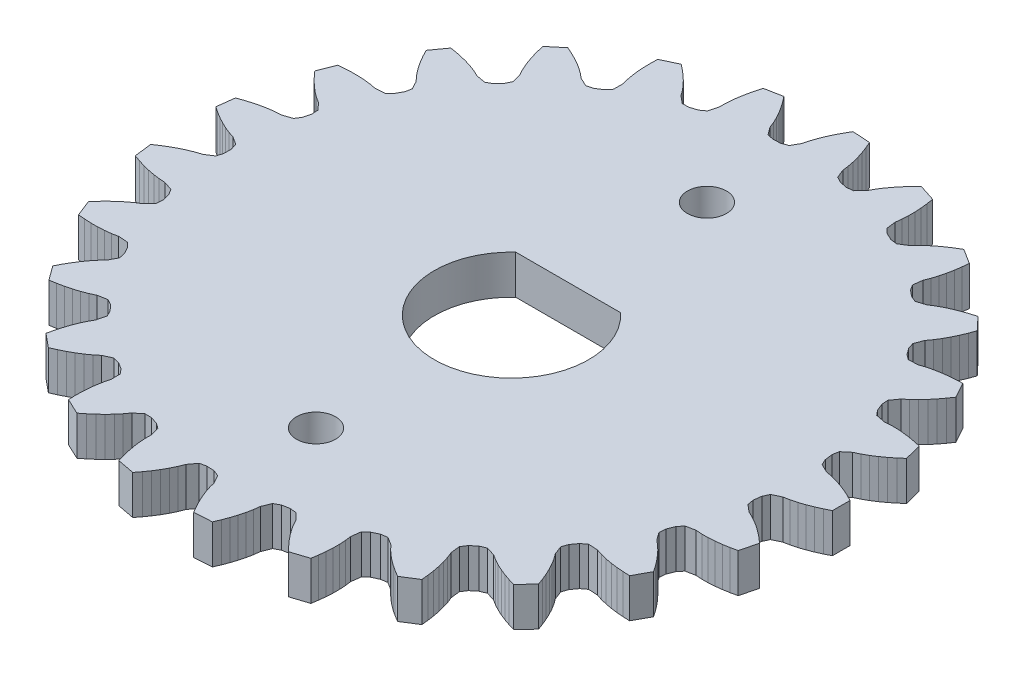
SolidWorks part; units mm, degrees
ref_plane "Спереди" through (0, 0, 0) normal (0, 0, 1) x (1, 0, 0)
ref_plane "Сверху" through (0, 0, 0) normal (0, 1, 0) x (1, 0, 0)
ref_plane "Справа" through (0, 0, 0) normal (1, 0, 0) x (0, 0, -1)
sketch "Эскиз1" plane through (0, 0, 0) normal (0, 1, 0) x (1, 0, 0)
  line L0 (32.9431, 20.3316) -> (33.081, 20.0302)
  line L1 (33.081, 20.0302) -> (33.5129, 19.8221)
  line L2 (33.5129, 19.8221) -> (33.824, 19.7632)
  line L3 (33.824, 19.7632) -> (34.1362, 19.6803)
  line L4 (34.1362, 19.6803) -> (34.4488, 19.5766)
  line L5 (34.4488, 19.5766) -> (34.7615, 19.454)
  line L6 (34.7615, 19.454) -> (35.0736, 19.3138)
  line L7 (35.0736, 19.3138) -> (35.3848, 19.1568)
  line L8 (35.3848, 19.1568) -> (35.3848, 18.2571)
  line L9 (35.3848, 18.2571) -> (35.0736, 18.1001)
  line L10 (35.0736, 18.1001) -> (34.7615, 17.9599)
  line L11 (34.7615, 17.9599) -> (34.4488, 17.8373)
  line L12 (34.4488, 17.8373) -> (34.1362, 17.7337)
  line L13 (34.1362, 17.7337) -> (33.824, 17.6507)
  line L14 (33.824, 17.6507) -> (33.5129, 17.5919)
  line L15 (33.5129, 17.5919) -> (33.081, 17.3838)
  line L16 (33.081, 17.3838) -> (32.9431, 17.0824)
  line L17 (32.9431, 17.0824) -> (32.8939, 16.6926)
  line L18 (32.8939, 16.6926) -> (32.9524, 16.3664)
  line L19 (32.9524, 16.3664) -> (33.319, 16.0574)
  line L20 (33.319, 16.0574) -> (33.6057, 15.9231)
  line L21 (33.6057, 15.9231) -> (33.8875, 15.7651)
  line L22 (33.8875, 15.7651) -> (34.1645, 15.5869)
  line L23 (34.1645, 15.5869) -> (34.4369, 15.3904)
  line L24 (34.4369, 15.3904) -> (34.7043, 15.177)
  line L25 (34.7043, 15.177) -> (34.9667, 14.9475)
  line L26 (34.9667, 14.9475) -> (34.743, 14.0761)
  line L27 (34.743, 14.0761) -> (34.4025, 14.0014)
  line L28 (34.4025, 14.0014) -> (34.0653, 13.9433)
  line L29 (34.0653, 13.9433) -> (33.732, 13.9023)
  line L30 (33.732, 13.9023) -> (33.4034, 13.8796)
  line L31 (33.4034, 13.8796) -> (33.0803, 13.8769)
  line L32 (33.0803, 13.8769) -> (32.7644, 13.8973)
  line L33 (32.7644, 13.8973) -> (32.2943, 13.8032)
  line L34 (32.2943, 13.8032) -> (32.0859, 13.5455)
  line L35 (32.0859, 13.5455) -> (31.9412, 13.1802)
  line L36 (31.9412, 13.1802) -> (31.9168, 12.8497)
  line L37 (31.9168, 12.8497) -> (32.195, 12.4593)
  line L38 (32.195, 12.4593) -> (32.4393, 12.2578)
  line L39 (32.4393, 12.2578) -> (32.6729, 12.0347)
  line L40 (32.6729, 12.0347) -> (32.897, 11.7933)
  line L41 (32.897, 11.7933) -> (33.1119, 11.5352)
  line L42 (33.1119, 11.5352) -> (33.3179, 11.262)
  line L43 (33.3179, 11.262) -> (33.5149, 10.9745)
  line L44 (33.5149, 10.9745) -> (33.0815, 10.1861)
  line L45 (33.0815, 10.1861) -> (32.7332, 10.1984)
  line L46 (32.7332, 10.1984) -> (32.3921, 10.2259)
  line L47 (32.3921, 10.2259) -> (32.0591, 10.2691)
  line L48 (32.0591, 10.2691) -> (31.7351, 10.3289)
  line L49 (31.7351, 10.3289) -> (31.4216, 10.4066)
  line L50 (31.4216, 10.4066) -> (31.1206, 10.5049)
  line L51 (31.1206, 10.5049) -> (30.6419, 10.5306)
  line L52 (30.6419, 10.5306) -> (30.3759, 10.3329)
  line L53 (30.3759, 10.3329) -> (30.145, 10.0151)
  line L54 (30.145, 10.0151) -> (30.0391, 9.701)
  line L55 (30.0391, 9.701) -> (30.2115, 9.2537)
  line L56 (30.2115, 9.2537) -> (30.398, 8.9978)
  line L57 (30.398, 8.9978) -> (30.5688, 8.7236)
  line L58 (30.5688, 8.7236) -> (30.7258, 8.434)
  line L59 (30.7258, 8.434) -> (30.8698, 8.1306)
  line L60 (30.8698, 8.1306) -> (31.0013, 7.8148)
  line L61 (31.0013, 7.8148) -> (31.1207, 7.4873)
  line L62 (31.1207, 7.4873) -> (30.5048, 6.8314)
  line L63 (30.5048, 6.8314) -> (30.1705, 6.93)
  line L64 (30.1705, 6.93) -> (29.847, 7.0415)
  line L65 (29.847, 7.0415) -> (29.5352, 7.1661)
  line L66 (29.5352, 7.1661) -> (29.2363, 7.3046)
  line L67 (29.2363, 7.3046) -> (28.9519, 7.4578)
  line L68 (28.9519, 7.4578) -> (28.6849, 7.6279)
  line L69 (28.6849, 7.6279) -> (28.2276, 7.7719)
  line L70 (28.2276, 7.7719) -> (27.9208, 7.6465)
  line L71 (27.9208, 7.6465) -> (27.6181, 7.3961)
  line L72 (27.6181, 7.3961) -> (27.4374, 7.1182)
  line L73 (27.4374, 7.1182) -> (27.4931, 6.642)
  line L74 (27.4931, 6.642) -> (27.6102, 6.3478)
  line L75 (27.6102, 6.3478) -> (27.7074, 6.0398)
  line L76 (27.7074, 6.0398) -> (27.7874, 5.7203)
  line L77 (27.7874, 5.7203) -> (27.8514, 5.3906)
  line L78 (27.8514, 5.3906) -> (27.9003, 5.0519)
  line L79 (27.9003, 5.0519) -> (27.9345, 4.705)
  line L80 (27.9345, 4.705) -> (27.1749, 4.223)
  line L81 (27.1749, 4.223) -> (26.8755, 4.4016)
  line L82 (26.8755, 4.4016) -> (26.5899, 4.59)
  line L83 (26.5899, 4.59) -> (26.3189, 4.7883)
  line L84 (26.3189, 4.7883) -> (26.0638, 4.9967)
  line L85 (26.0638, 4.9967) -> (25.8265, 5.2159)
  line L86 (25.8265, 5.2159) -> (25.6101, 5.447)
  line L87 (25.6101, 5.447) -> (25.203, 5.7002)
  line L88 (25.203, 5.7002) -> (24.8747, 5.6551)
  line L89 (24.8747, 5.6551) -> (24.5192, 5.4878)
  line L90 (24.5192, 5.4878) -> (24.2751, 5.2636)
  line L91 (24.2751, 5.2636) -> (24.2107, 4.7885)
  line L92 (24.2107, 4.7885) -> (24.2508, 4.4745)
  line L93 (24.2508, 4.4745) -> (24.2684, 4.1519)
  line L94 (24.2684, 4.1519) -> (24.2664, 3.8225)
  line L95 (24.2664, 3.8225) -> (24.2465, 3.4873)
  line L96 (24.2465, 3.4873) -> (24.2096, 3.1471)
  line L97 (24.2096, 3.1471) -> (24.1564, 2.8026)
  line L98 (24.1564, 2.8026) -> (23.3008, 2.5246)
  line L99 (23.3008, 2.5246) -> (23.0553, 2.7721)
  line L100 (23.0553, 2.7721) -> (22.8255, 3.0256)
  line L101 (22.8255, 3.0256) -> (22.6123, 3.285)
  line L102 (22.6123, 3.285) -> (22.4171, 3.5504)
  line L103 (22.4171, 3.5504) -> (22.2417, 3.8217)
  line L104 (22.2417, 3.8217) -> (22.0896, 4.0993)
  line L105 (22.0896, 4.0993) -> (21.7583, 4.4458)
  line L106 (21.7583, 4.4458) -> (21.429, 4.4837)
  line L107 (21.429, 4.4837) -> (21.0431, 4.4101)
  line L108 (21.0431, 4.4101) -> (20.7509, 4.2536)
  line L109 (20.7509, 4.2536) -> (20.5704, 3.8095)
  line L110 (20.5704, 3.8095) -> (20.5312, 3.4953)
  line L111 (20.5312, 3.4953) -> (20.468, 3.1786)
  line L112 (20.468, 3.1786) -> (20.3842, 2.86)
  line L113 (20.3842, 2.86) -> (20.2815, 2.5403)
  line L114 (20.2815, 2.5403) -> (20.1611, 2.22)
  line L115 (20.1611, 2.22) -> (20.024, 1.8995)
  line L116 (20.024, 1.8995) -> (19.1261, 1.843)
  line L117 (19.1261, 1.843) -> (18.9498, 2.1438)
  line L118 (18.9498, 2.1438) -> (18.7903, 2.4465)
  line L119 (18.7903, 2.4465) -> (18.6483, 2.7508)
  line L120 (18.6483, 2.7508) -> (18.5252, 3.0563)
  line L121 (18.5252, 3.0563) -> (18.4228, 3.3627)
  line L122 (18.4228, 3.3627) -> (18.3446, 3.6695)
  line L123 (18.3446, 3.6695) -> (18.1098, 4.0875)
  line L124 (18.1098, 4.0875) -> (17.8003, 4.2061)
  line L125 (17.8003, 4.2061) -> (17.4082, 4.2308)
  line L126 (17.4082, 4.2308) -> (17.0863, 4.1519)
  line L127 (17.0863, 4.1519) -> (16.801, 3.7666)
  line L128 (16.801, 3.7666) -> (16.6849, 3.472)
  line L129 (16.6849, 3.472) -> (16.5449, 3.1809)
  line L130 (16.5449, 3.1809) -> (16.3845, 2.8932)
  line L131 (16.3845, 2.8932) -> (16.2055, 2.6091)
  line L132 (16.2055, 2.6091) -> (16.0093, 2.3288)
  line L133 (16.0093, 2.3288) -> (15.7967, 2.0525)
  line L134 (15.7967, 2.0525) -> (14.913, 2.2211)
  line L135 (14.913, 2.2211) -> (14.8171, 2.5562)
  line L136 (14.8171, 2.5562) -> (14.7378, 2.8891)
  line L137 (14.7378, 2.8891) -> (14.676, 3.2191)
  line L138 (14.676, 3.2191) -> (14.6328, 3.5457)
  line L139 (14.6328, 3.5457) -> (14.6098, 3.8679)
  line L140 (14.6098, 3.8679) -> (14.6103, 4.1845)
  line L141 (14.6103, 4.1845) -> (14.4868, 4.6478)
  line L142 (14.4868, 4.6478) -> (14.2166, 4.8396)
  line L143 (14.2166, 4.8396) -> (13.8429, 4.961)
  line L144 (13.8429, 4.961) -> (13.5115, 4.9646)
  line L145 (13.5115, 4.9646) -> (13.1393, 4.6624)
  line L146 (13.1393, 4.6624) -> (12.9536, 4.406)
  line L147 (12.9536, 4.406) -> (12.7457, 4.1588)
  line L148 (12.7457, 4.1588) -> (12.5187, 3.9201)
  line L149 (12.5187, 3.9201) -> (12.2747, 3.6894)
  line L150 (12.2747, 3.6894) -> (12.0149, 3.4667)
  line L151 (12.0149, 3.4667) -> (11.7404, 3.2519)
  line L152 (11.7404, 3.2519) -> (10.9263, 3.635)
  line L153 (10.9263, 3.635) -> (10.9167, 3.9834)
  line L154 (10.9167, 3.9834) -> (10.9228, 4.3256)
  line L155 (10.9228, 4.3256) -> (10.945, 4.6606)
  line L156 (10.945, 4.6606) -> (10.9843, 4.9877)
  line L157 (10.9843, 4.9877) -> (11.0422, 5.3055)
  line L158 (11.0422, 5.3055) -> (11.1214, 5.612)
  line L159 (11.1214, 5.612) -> (11.117, 6.0914)
  line L160 (11.117, 6.0914) -> (10.903, 6.3445)
  line L161 (10.903, 6.3445) -> (10.5713, 6.555)
  line L162 (10.5713, 6.555) -> (10.2512, 6.6409)
  line L163 (10.2512, 6.6409) -> (9.8155, 6.4407)
  line L164 (9.8155, 6.4407) -> (9.5719, 6.2386)
  line L165 (9.5719, 6.2386) -> (9.309, 6.0509)
  line L166 (9.309, 6.0509) -> (9.0298, 5.876)
  line L167 (9.0298, 5.876) -> (8.7361, 5.7133)
  line L168 (8.7361, 5.7133) -> (8.4291, 5.5622)
  line L169 (8.4291, 5.5622) -> (8.1097, 5.4225)
  line L170 (8.1097, 5.4225) -> (7.4165, 5.9959)
  line L171 (7.4165, 5.9959) -> (7.4939, 6.3358)
  line L172 (7.4939, 6.3358) -> (7.5848, 6.6657)
  line L173 (7.5848, 6.6657) -> (7.6897, 6.9847)
  line L174 (7.6897, 6.9847) -> (7.8091, 7.2917)
  line L175 (7.8091, 7.2917) -> (7.9442, 7.5851)
  line L176 (7.9442, 7.5851) -> (8.0971, 7.8623)
  line L177 (8.0971, 7.8623) -> (8.2121, 8.3278)
  line L178 (8.2121, 8.3278) -> (8.0677, 8.6261)
  line L179 (8.0677, 8.6261) -> (7.7988, 8.9125)
  line L180 (7.7988, 8.9125) -> (7.5101, 9.0753)
  line L181 (7.5101, 9.0753) -> (7.0384, 8.9898)
  line L182 (7.0384, 8.9898) -> (6.7521, 8.8545)
  line L183 (6.7521, 8.8545) -> (6.4508, 8.7381)
  line L184 (6.4508, 8.7381) -> (6.1369, 8.6382)
  line L185 (6.1369, 8.6382) -> (5.8119, 8.5536)
  line L186 (5.8119, 8.5536) -> (5.477, 8.4836)
  line L187 (5.477, 8.4836) -> (5.1329, 8.4277)
  line L188 (5.1329, 8.4277) -> (4.6041, 9.1555)
  line L189 (4.6041, 9.1555) -> (4.7636, 9.4655)
  line L190 (4.7636, 9.4655) -> (4.9337, 9.7624)
  line L191 (4.9337, 9.7624) -> (5.1146, 10.0453)
  line L192 (5.1146, 10.0453) -> (5.3066, 10.313)
  line L193 (5.3066, 10.313) -> (5.5104, 10.5636)
  line L194 (5.5104, 10.5636) -> (5.7275, 10.7941)
  line L195 (5.7275, 10.7941) -> (5.9546, 11.2163)
  line L196 (5.9546, 11.2163) -> (5.8889, 11.5411)
  line L197 (5.8889, 11.5411) -> (5.6997, 11.8854)
  line L198 (5.6997, 11.8854) -> (5.4606, 12.1149)
  line L199 (5.4606, 12.1149) -> (4.9824, 12.1494)
  line L200 (4.9824, 12.1494) -> (4.6715, 12.0896)
  line L201 (4.6715, 12.0896) -> (4.3507, 12.0518)
  line L202 (4.3507, 12.0518) -> (4.0218, 12.0331)
  line L203 (4.0218, 12.0331) -> (3.686, 12.0319)
  line L204 (3.686, 12.0319) -> (3.3442, 12.0474)
  line L205 (3.3442, 12.0474) -> (2.997, 12.0788)
  line L206 (2.997, 12.0788) -> (2.6658, 12.9153)
  line L207 (2.6658, 12.9153) -> (2.8974, 13.1759)
  line L208 (2.8974, 13.1759) -> (3.136, 13.4212)
  line L209 (3.136, 13.4212) -> (3.3815, 13.6502)
  line L210 (3.3815, 13.6502) -> (3.6341, 13.8617)
  line L211 (3.6341, 13.8617) -> (3.8938, 14.0538)
  line L212 (3.8938, 14.0538) -> (4.1614, 14.223)
  line L213 (4.1614, 14.223) -> (4.4864, 14.5755)
  line L214 (4.4864, 14.5755) -> (4.5036, 14.9064)
  line L215 (4.5036, 14.9064) -> (4.4059, 15.287)
  line L216 (4.4059, 15.287) -> (4.2313, 15.5687)
  line L217 (4.2313, 15.5687) -> (3.7768, 15.721)
  line L218 (3.7768, 15.721) -> (3.4607, 15.7404)
  line L219 (3.4607, 15.7404) -> (3.1406, 15.7836)
  line L220 (3.1406, 15.7836) -> (2.8174, 15.8473)
  line L221 (2.8174, 15.8473) -> (2.4919, 15.9297)
  line L222 (2.4919, 15.9297) -> (2.1646, 16.0297)
  line L223 (2.1646, 16.0297) -> (1.8362, 16.1464)
  line L224 (1.8362, 16.1464) -> (1.7234, 17.039)
  line L225 (1.7234, 17.039) -> (2.0125, 17.2338)
  line L226 (2.0125, 17.2338) -> (2.3046, 17.412)
  line L227 (2.3046, 17.412) -> (2.5994, 17.5728)
  line L228 (2.5994, 17.5728) -> (2.8966, 17.7149)
  line L229 (2.8966, 17.7149) -> (3.196, 17.8363)
  line L230 (3.196, 17.8363) -> (3.4972, 17.9337)
  line L231 (3.4972, 17.9337) -> (3.8997, 18.1942)
  line L232 (3.8997, 18.1942) -> (3.9986, 18.5105)
  line L233 (3.9986, 18.5105) -> (3.9986, 18.9034)
  line L234 (3.9986, 18.9034) -> (3.8997, 19.2197)
  line L235 (3.8997, 19.2197) -> (3.4972, 19.4803)
  line L236 (3.4972, 19.4803) -> (3.196, 19.5777)
  line L237 (3.196, 19.5777) -> (2.8966, 19.6991)
  line L238 (2.8966, 19.6991) -> (2.5994, 19.8411)
  line L239 (2.5994, 19.8411) -> (2.3046, 20.0019)
  line L240 (2.3046, 20.0019) -> (2.0125, 20.1802)
  line L241 (2.0125, 20.1802) -> (1.7234, 20.3749)
  line L242 (1.7234, 20.3749) -> (1.8362, 21.2675)
  line L243 (1.8362, 21.2675) -> (2.1646, 21.3843)
  line L244 (2.1646, 21.3843) -> (2.4919, 21.4843)
  line L245 (2.4919, 21.4843) -> (2.8174, 21.5667)
  line L246 (2.8174, 21.5667) -> (3.1406, 21.6304)
  line L247 (3.1406, 21.6304) -> (3.4607, 21.6735)
  line L248 (3.4607, 21.6735) -> (3.7768, 21.6929)
  line L249 (3.7768, 21.6929) -> (4.2313, 21.8452)
  line L250 (4.2313, 21.8452) -> (4.4059, 22.127)
  line L251 (4.4059, 22.127) -> (4.5036, 22.5075)
  line L252 (4.5036, 22.5075) -> (4.4864, 22.8385)
  line L253 (4.4864, 22.8385) -> (4.1614, 23.191)
  line L254 (4.1614, 23.191) -> (3.8938, 23.3602)
  line L255 (3.8938, 23.3602) -> (3.6341, 23.5522)
  line L256 (3.6341, 23.5522) -> (3.3815, 23.7637)
  line L257 (3.3815, 23.7637) -> (3.136, 23.9928)
  line L258 (3.136, 23.9928) -> (2.8974, 24.2381)
  line L259 (2.8974, 24.2381) -> (2.6658, 24.4986)
  line L260 (2.6658, 24.4986) -> (2.997, 25.3351)
  line L261 (2.997, 25.3351) -> (3.3442, 25.3665)
  line L262 (3.3442, 25.3665) -> (3.686, 25.382)
  line L263 (3.686, 25.382) -> (4.0218, 25.3809)
  line L264 (4.0218, 25.3809) -> (4.3507, 25.3622)
  line L265 (4.3507, 25.3622) -> (4.6715, 25.3244)
  line L266 (4.6715, 25.3244) -> (4.9824, 25.2646)
  line L267 (4.9824, 25.2646) -> (5.4606, 25.299)
  line L268 (5.4606, 25.299) -> (5.6997, 25.5285)
  line L269 (5.6997, 25.5285) -> (5.8889, 25.8728)
  line L270 (5.8889, 25.8728) -> (5.9546, 26.1977)
  line L271 (5.9546, 26.1977) -> (5.7275, 26.6199)
  line L272 (5.7275, 26.6199) -> (5.5104, 26.8504)
  line L273 (5.5104, 26.8504) -> (5.3066, 27.101)
  line L274 (5.3066, 27.101) -> (5.1146, 27.3686)
  line L275 (5.1146, 27.3686) -> (4.9337, 27.6515)
  line L276 (4.9337, 27.6515) -> (4.7636, 27.9485)
  line L277 (4.7636, 27.9485) -> (4.6041, 28.2584)
  line L278 (4.6041, 28.2584) -> (5.1329, 28.9863)
  line L279 (5.1329, 28.9863) -> (5.477, 28.9304)
  line L280 (5.477, 28.9304) -> (5.8119, 28.8603)
  line L281 (5.8119, 28.8603) -> (6.1369, 28.7757)
  line L282 (6.1369, 28.7757) -> (6.4508, 28.6758)
  line L283 (6.4508, 28.6758) -> (6.7521, 28.5594)
  line L284 (6.7521, 28.5594) -> (7.0384, 28.4242)
  line L285 (7.0384, 28.4242) -> (7.5101, 28.3386)
  line L286 (7.5101, 28.3386) -> (7.7988, 28.5015)
  line L287 (7.7988, 28.5015) -> (8.0677, 28.7879)
  line L288 (8.0677, 28.7879) -> (8.2121, 29.0862)
  line L289 (8.2121, 29.0862) -> (8.0971, 29.5516)
  line L290 (8.0971, 29.5516) -> (7.9442, 29.8288)
  line L291 (7.9442, 29.8288) -> (7.8091, 30.1222)
  line L292 (7.8091, 30.1222) -> (7.6897, 30.4293)
  line L293 (7.6897, 30.4293) -> (7.5848, 30.7483)
  line L294 (7.5848, 30.7483) -> (7.4939, 31.0782)
  line L295 (7.4939, 31.0782) -> (7.4165, 31.418)
  line L296 (7.4165, 31.418) -> (8.1097, 31.9915)
  line L297 (8.1097, 31.9915) -> (8.4291, 31.8518)
  line L298 (8.4291, 31.8518) -> (8.7361, 31.7007)
  line L299 (8.7361, 31.7007) -> (9.0298, 31.5379)
  line L300 (9.0298, 31.5379) -> (9.309, 31.3631)
  line L301 (9.309, 31.3631) -> (9.5719, 31.1754)
  line L302 (9.5719, 31.1754) -> (9.8155, 30.9732)
  line L303 (9.8155, 30.9732) -> (10.2512, 30.773)
  line L304 (10.2512, 30.773) -> (10.5713, 30.859)
  line L305 (10.5713, 30.859) -> (10.903, 31.0695)
  line L306 (10.903, 31.0695) -> (11.117, 31.3225)
  line L307 (11.117, 31.3225) -> (11.1214, 31.8019)
  line L308 (11.1214, 31.8019) -> (11.0422, 32.1085)
  line L309 (11.0422, 32.1085) -> (10.9843, 32.4263)
  line L310 (10.9843, 32.4263) -> (10.945, 32.7533)
  line L311 (10.945, 32.7533) -> (10.9228, 33.0884)
  line L312 (10.9228, 33.0884) -> (10.9167, 33.4305)
  line L313 (10.9167, 33.4305) -> (10.9263, 33.779)
  line L314 (10.9263, 33.779) -> (11.7404, 34.162)
  line L315 (11.7404, 34.162) -> (12.0149, 33.9473)
  line L316 (12.0149, 33.9473) -> (12.2747, 33.7246)
  line L317 (12.2747, 33.7246) -> (12.5187, 33.4939)
  line L318 (12.5187, 33.4939) -> (12.7457, 33.2551)
  line L319 (12.7457, 33.2551) -> (12.9536, 33.0079)
  line L320 (12.9536, 33.0079) -> (13.1393, 32.7515)
  line L321 (13.1393, 32.7515) -> (13.5115, 32.4493)
  line L322 (13.5115, 32.4493) -> (13.8429, 32.4529)
  line L323 (13.8429, 32.4529) -> (14.2166, 32.5743)
  line L324 (14.2166, 32.5743) -> (14.4868, 32.7662)
  line L325 (14.4868, 32.7662) -> (14.6103, 33.2295)
  line L326 (14.6103, 33.2295) -> (14.6098, 33.5461)
  line L327 (14.6098, 33.5461) -> (14.6328, 33.8683)
  line L328 (14.6328, 33.8683) -> (14.676, 34.1948)
  line L329 (14.676, 34.1948) -> (14.7378, 34.5249)
  line L330 (14.7378, 34.5249) -> (14.8171, 34.8578)
  line L331 (14.8171, 34.8578) -> (14.913, 35.1929)
  line L332 (14.913, 35.1929) -> (15.7967, 35.3615)
  line L333 (15.7967, 35.3615) -> (16.0093, 35.0852)
  line L334 (16.0093, 35.0852) -> (16.2055, 34.8049)
  line L335 (16.2055, 34.8049) -> (16.3845, 34.5207)
  line L336 (16.3845, 34.5207) -> (16.5449, 34.233)
  line L337 (16.5449, 34.233) -> (16.6849, 33.9419)
  line L338 (16.6849, 33.9419) -> (16.801, 33.6474)
  line L339 (16.801, 33.6474) -> (17.0863, 33.2621)
  line L340 (17.0863, 33.2621) -> (17.4082, 33.1832)
  line L341 (17.4082, 33.1832) -> (17.8003, 33.2078)
  line L342 (17.8003, 33.2078) -> (18.1098, 33.3265)
  line L343 (18.1098, 33.3265) -> (18.3446, 33.7445)
  line L344 (18.3446, 33.7445) -> (18.4228, 34.0512)
  line L345 (18.4228, 34.0512) -> (18.5252, 34.3576)
  line L346 (18.5252, 34.3576) -> (18.6483, 34.6632)
  line L347 (18.6483, 34.6632) -> (18.7903, 34.9675)
  line L348 (18.7903, 34.9675) -> (18.9498, 35.2702)
  line L349 (18.9498, 35.2702) -> (19.1261, 35.5709)
  line L350 (19.1261, 35.5709) -> (20.024, 35.5144)
  line L351 (20.024, 35.5144) -> (20.1611, 35.194)
  line L352 (20.1611, 35.194) -> (20.2815, 34.8737)
  line L353 (20.2815, 34.8737) -> (20.3842, 34.5539)
  line L354 (20.3842, 34.5539) -> (20.468, 34.2354)
  line L355 (20.468, 34.2354) -> (20.5312, 33.9186)
  line L356 (20.5312, 33.9186) -> (20.5704, 33.6044)
  line L357 (20.5704, 33.6044) -> (20.7509, 33.1603)
  line L358 (20.7509, 33.1603) -> (21.0431, 33.0038)
  line L359 (21.0431, 33.0038) -> (21.429, 32.9302)
  line L360 (21.429, 32.9302) -> (21.7583, 32.9681)
  line L361 (21.7583, 32.9681) -> (22.0896, 33.3146)
  line L362 (22.0896, 33.3146) -> (22.2417, 33.5923)
  line L363 (22.2417, 33.5923) -> (22.4171, 33.8636)
  line L364 (22.4171, 33.8636) -> (22.6123, 34.1289)
  line L365 (22.6123, 34.1289) -> (22.8255, 34.3884)
  line L366 (22.8255, 34.3884) -> (23.0553, 34.6419)
  line L367 (23.0553, 34.6419) -> (23.3008, 34.8894)
  line L368 (23.3008, 34.8894) -> (24.1564, 34.6113)
  line L369 (24.1564, 34.6113) -> (24.2096, 34.2668)
  line L370 (24.2096, 34.2668) -> (24.2465, 33.9267)
  line L371 (24.2465, 33.9267) -> (24.2664, 33.5914)
  line L372 (24.2664, 33.5914) -> (24.2684, 33.262)
  line L373 (24.2684, 33.262) -> (24.2508, 32.9395)
  line L374 (24.2508, 32.9395) -> (24.2107, 32.6254)
  line L375 (24.2107, 32.6254) -> (24.2751, 32.1504)
  line L376 (24.2751, 32.1504) -> (24.5192, 31.9262)
  line L377 (24.5192, 31.9262) -> (24.8747, 31.7589)
  line L378 (24.8747, 31.7589) -> (25.203, 31.7137)
  line L379 (25.203, 31.7137) -> (25.6101, 31.9669)
  line L380 (25.6101, 31.9669) -> (25.8265, 32.1981)
  line L381 (25.8265, 32.1981) -> (26.0638, 32.4172)
  line L382 (26.0638, 32.4172) -> (26.3189, 32.6256)
  line L383 (26.3189, 32.6256) -> (26.5899, 32.8239)
  line L384 (26.5899, 32.8239) -> (26.8755, 33.0123)
  line L385 (26.8755, 33.0123) -> (27.1749, 33.191)
  line L386 (27.1749, 33.191) -> (27.9345, 32.7089)
  line L387 (27.9345, 32.7089) -> (27.9003, 32.362)
  line L388 (27.9003, 32.362) -> (27.8514, 32.0233)
  line L389 (27.8514, 32.0233) -> (27.7874, 31.6937)
  line L390 (27.7874, 31.6937) -> (27.7074, 31.3741)
  line L391 (27.7074, 31.3741) -> (27.6102, 31.0661)
  line L392 (27.6102, 31.0661) -> (27.4931, 30.7719)
  line L393 (27.4931, 30.7719) -> (27.4374, 30.2957)
  line L394 (27.4374, 30.2957) -> (27.6181, 30.0179)
  line L395 (27.6181, 30.0179) -> (27.9208, 29.7674)
  line L396 (27.9208, 29.7674) -> (28.2276, 29.6421)
  line L397 (28.2276, 29.6421) -> (28.6849, 29.7861)
  line L398 (28.6849, 29.7861) -> (28.9519, 29.9561)
  line L399 (28.9519, 29.9561) -> (29.2363, 30.1094)
  line L400 (29.2363, 30.1094) -> (29.5352, 30.2478)
  line L401 (29.5352, 30.2478) -> (29.847, 30.3725)
  line L402 (29.847, 30.3725) -> (30.1705, 30.4839)
  line L403 (30.1705, 30.4839) -> (30.5048, 30.5825)
  line L404 (30.5048, 30.5825) -> (31.1207, 29.9267)
  line L405 (31.1207, 29.9267) -> (31.0013, 29.5992)
  line L406 (31.0013, 29.5992) -> (30.8698, 29.2833)
  line L407 (30.8698, 29.2833) -> (30.7258, 28.9799)
  line L408 (30.7258, 28.9799) -> (30.5688, 28.6903)
  line L409 (30.5688, 28.6903) -> (30.398, 28.4161)
  line L410 (30.398, 28.4161) -> (30.2115, 28.1603)
  line L411 (30.2115, 28.1603) -> (30.0391, 27.7129)
  line L412 (30.0391, 27.7129) -> (30.145, 27.3989)
  line L413 (30.145, 27.3989) -> (30.3759, 27.081)
  line L414 (30.3759, 27.081) -> (30.6419, 26.8833)
  line L415 (30.6419, 26.8833) -> (31.1206, 26.909)
  line L416 (31.1206, 26.909) -> (31.4216, 27.0073)
  line L417 (31.4216, 27.0073) -> (31.7351, 27.0851)
  line L418 (31.7351, 27.0851) -> (32.0591, 27.1448)
  line L419 (32.0591, 27.1448) -> (32.3921, 27.188)
  line L420 (32.3921, 27.188) -> (32.7332, 27.2155)
  line L421 (32.7332, 27.2155) -> (33.0815, 27.2279)
  line L422 (33.0815, 27.2279) -> (33.5149, 26.4395)
  line L423 (33.5149, 26.4395) -> (33.3179, 26.152)
  line L424 (33.3179, 26.152) -> (33.1119, 25.8787)
  line L425 (33.1119, 25.8787) -> (32.897, 25.6207)
  line L426 (32.897, 25.6207) -> (32.6729, 25.3792)
  line L427 (32.6729, 25.3792) -> (32.4393, 25.1561)
  line L428 (32.4393, 25.1561) -> (32.195, 24.9547)
  line L429 (32.195, 24.9547) -> (31.9168, 24.5643)
  line L430 (31.9168, 24.5643) -> (31.9412, 24.2337)
  line L431 (31.9412, 24.2337) -> (32.0859, 23.8685)
  line L432 (32.0859, 23.8685) -> (32.2943, 23.6108)
  line L433 (32.2943, 23.6108) -> (32.7644, 23.5167)
  line L434 (32.7644, 23.5167) -> (33.0803, 23.537)
  line L435 (33.0803, 23.537) -> (33.4034, 23.5343)
  line L436 (33.4034, 23.5343) -> (33.732, 23.5117)
  line L437 (33.732, 23.5117) -> (34.0653, 23.4707)
  line L438 (34.0653, 23.4707) -> (34.4025, 23.4125)
  line L439 (34.4025, 23.4125) -> (34.743, 23.3378)
  line L440 (34.743, 23.3378) -> (34.9667, 22.4664)
  line L441 (34.9667, 22.4664) -> (34.7043, 22.237)
  line L442 (34.7043, 22.237) -> (34.4369, 22.0235)
  line L443 (34.4369, 22.0235) -> (34.1645, 21.827)
  line L444 (34.1645, 21.827) -> (33.8875, 21.6489)
  line L445 (33.8875, 21.6489) -> (33.6057, 21.4909)
  line L446 (33.6057, 21.4909) -> (33.319, 21.3565)
  line L447 (33.319, 21.3565) -> (32.9524, 21.0476)
  line L448 (32.9524, 21.0476) -> (32.8939, 20.7213)
  line L449 (32.8939, 20.7213) -> (32.9431, 20.3316)
extrude "Бобышка-Вытянуть1" add sketch "Эскиз1" along normal blind 2
sketch "Эскиз2" plane through (0, 2, 0) normal (0, 1, 0) x (1, 0, 0)
  line L0 (15.8339, 21.607) -> (21.1977, 21.607)
  line L3 (18.5158, 18.707) -> (18.5158, 36.7524) construction
  line L4 (18.5158, 18.707) -> (18.5158, -1.4367) construction
  line L5 (18.5158, 18.707) -> (42.4119, 18.707) construction
  line L6 (18.5158, 18.707) -> (-1.4391, 18.707) construction
  circle A0 centre (18.5158, 18.707) radius 10 construction
  arc A1 (15.8339, 21.607) -> (21.1977, 21.607) centre (18.5158, 18.707) ccw
  circle A2 centre (18.5158, 28.707) radius 1
  circle A3 centre (18.5158, 8.707) radius 1
  dimension "D1" = 7.9
  dimension "D3" = 20
  dimension "D4" = 2
  dimension "D5" = 2
  dimension "D2" = 2.9
extrude "Вырез-Вытянуть1" cut sketch "Эскиз2" against normal blind 10
